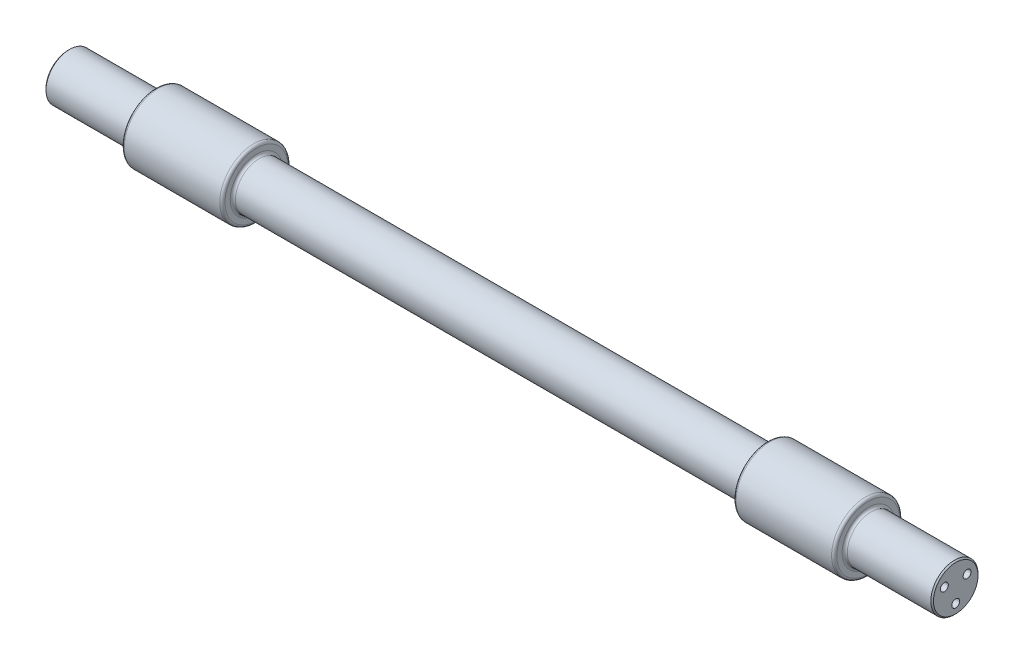
SolidWorks part; units mm, degrees
material "1023 Carbon Steel Sheet (SS)"
ref_plane "Front Plane" through (0, 0, 0) normal (0, 0, 1) x (1, 0, 0)
ref_plane "Top Plane" through (0, 0, 0) normal (0, 1, 0) x (1, 0, 0)
ref_plane "Right Plane" through (0, 0, 0) normal (1, 0, 0) x (0, 0, -1)
sketch "Sketch1" plane through (0, 0, 0) normal (0, 0, 1) x (1, 0, 0)
  line L0 (0, 0) -> (-3385, 0)
  line L1 (-3385, 0) -> (-3385, 90)
  line L2 (-3385, 90) -> (-3051.5, 90)
  line L3 (-3051.5, 90) -> (-3051.5, 130)
  line L4 (-3051.5, 130) -> (-2667.25, 130)
  line L5 (-2667.25, 130) -> (-2667.25, 90)
  line L6 (-2667.25, 90) -> (-717.75, 90)
  line L7 (-717.75, 90) -> (-717.75, 130)
  line L8 (-717.75, 130) -> (-333.5, 130)
  line L9 (-333.5, 130) -> (-333.5, 90)
  line L10 (-333.5, 90) -> (0, 90)
  line L11 (0, 90) -> (0, 0)
  dimension "D1" = 3385
  dimension "D2" = 333.5
  dimension "D3" = 333.5
  dimension "D4" = 384.25
  dimension "D5" = 384.25
  dimension "D6" = 130
  dimension "D7" = 90
revolve "Revolve1" add sketch "Sketch1" angle 360 about L0
sketch "Sketch2" plane through (-3385, 0, 0) normal (-1, 0, 0) x (0, 0, 1)
  circle A0 centre (0, 0) radius 50 construction
  circle A1 centre (0, -50) radius 15
  dimension "D1" = 100
  dimension "D2" = 30
extrude "Cut-Extrude1" cut sketch "Sketch2" against normal blind 50
pattern_circular "CirPattern1" count 3 over 360 about axis through (0, 0, 0) along (1, 0, 0) of "Cut-Extrude1"
ref_plane "Plane1" through (-1692.5, 0, 0) normal (-1, 0, 0) x (0, 0, 1)
mirror "Mirror1" about plane through (-1692.5, 0, 0) normal (-1, 0, 0) of "Cut-Extrude1", "CirPattern1"
fillet "Fillet1" radius 10 8 edges at (-2667.25, 90, 0) (-2667.25, 130, 0) (-3051.5, 130, 0) (-3051.5, 90, 0) (-717.75, 130, 0) (-717.75, 90, 0) (-333.5, 90, 0) (-333.5, 130, 0)
chamfer "Chamfer1" distance 5 angle 45 2 edges at (-3385, 90, 0) (0, 90, 0)
